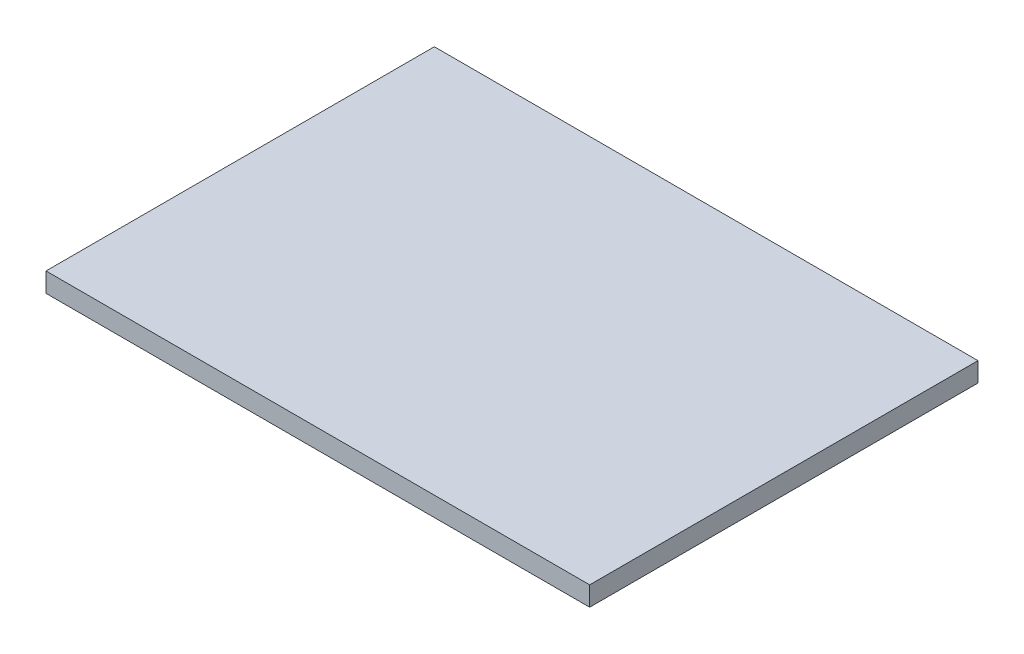
SolidWorks part; units mm, degrees
ref_plane "Front Plane" through (0, 0, 0) normal (0, 0, 1) x (1, 0, 0)
ref_plane "Top Plane" through (0, 0, 0) normal (0, 1, 0) x (1, 0, 0)
ref_plane "Right Plane" through (0, 0, 0) normal (1, 0, 0) x (0, 0, -1)
sketch "Sketch1" plane through (0, 0, 0) normal (0, 1, 0) x (1, 0, 0)
  line L1 (-79.3967, 30.7561) -> (620.6033, 30.7561)
  line L2 (-79.3967, 30.7561) -> (-79.3967, -469.2439)
  line L3 (-79.3967, -469.2439) -> (620.6033, -469.2439)
  line L4 (620.6033, 30.7561) -> (620.6033, -469.2439)
  dimension "D1" = 700
  dimension "500" = 500
extrude "Boss-Extrude1" add sketch "Sketch1" along normal blind 25 contours L1 L4 L3 L2
